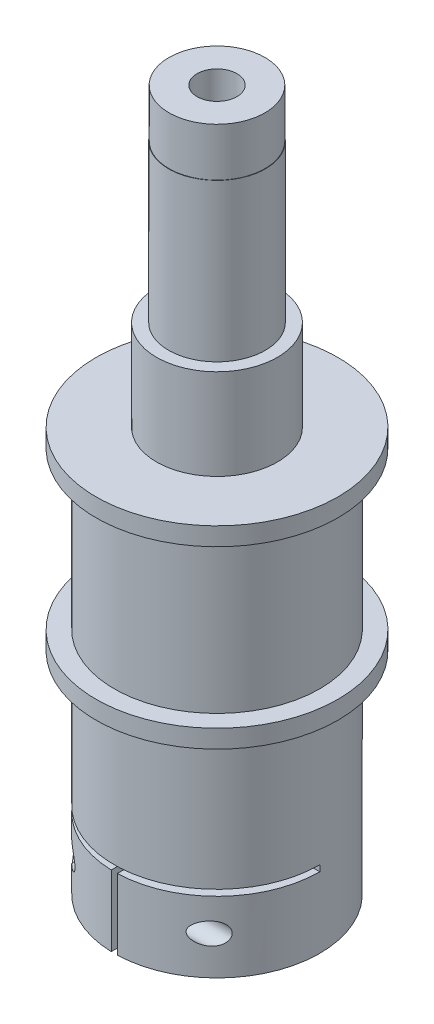
SolidWorks part; units mm, degrees
material "6061 Alloy"
ref_plane "Front Plane" through (0, 0, 0) normal (0, 0, 1) x (1, 0, 0)
ref_plane "Top Plane" through (0, 0, 0) normal (0, 1, 0) x (1, 0, 0)
ref_plane "Right Plane" through (0, 0, 0) normal (1, 0, 0) x (0, 0, -1)
sketch "Sketch1" plane through (0, 0, 0) normal (0, 0, 1) x (1, 0, 0)
  line L2 (-8.5, -17.45) -> (-8.5, 0)
  line L3 (-8.5, 0) -> (-10, 0)
  line L4 (-10, 0) -> (-10, 1.5)
  line L5 (-10, 1.5) -> (-8.5, 1.5)
  line L6 (-8.5, 1.5) -> (-8.5, 14.5)
  line L7 (-8.5, 14.5) -> (-10, 14.5)
  line L8 (-10, 14.5) -> (-10, 16)
  line L10 (0, 40.5) -> (0, 2.55)
  line L11 (-4, -17.45) -> (-8.5, -17.45)
  line L12 (-4, 2.55) -> (-4, -17.45)
  line L13 (0, 2.55) -> (-4, 2.55)
  line L15 (-3.9688, 36.5) -> (-3.9688, 40.5)
  line L16 (-3.9688, 40.5) -> (0, 40.5)
  line L17 (-10, 16) -> (-5, 16)
  line L19 (-4, 36.5) -> (-3.9688, 36.5)
  line L20 (-4, 36.5) -> (-4, 23.5)
  line L21 (-4, 23.5) -> (-5, 23.5)
  line L22 (-5, 23.5) -> (-5, 16)
  point P0 (0, 0)
  dimension "D1" = 8.5
  dimension "D2" = 1.5
  dimension "D3" = 17.45
  dimension "D4" = 1.5
  dimension "D5" = 4
  dimension "D6" = 20
  dimension "D7" = 3.9688
  dimension "D8" = 10
  dimension "D9" = 16
  dimension "D10" = 4
  dimension "D11" = 4
  dimension "D12" = 5
  dimension "D13" = 7.5
  dimension "D14" = 13
revolve "Revolve1" add sketch "Sketch1" angle 360 about L10
ref_plane "Plane1" through (-8.5, 0, 0) normal (-1, 0, 0) x (0, 0, 1)
hole_wizard "CBORE for M1.6 SHCS1" positions "Sketch2" profile "Sketch3" counterbore size "M1.6" standard "ANSI Metric" end condition through all
sketch "Sketch2" plane through (-8.5, 0, 0) normal (1, 0, 0) x (0, 0, -1)
  line L0 (-8.5, -17.45) -> (8.5, -17.45) construction
  point P0 (-6.25, -14.275)
  dimension "D1" = 6.25
  dimension "D2" = 3.175
sketch "Sketch3" plane through (-8.5, -14.275, 6.25) normal (0, 1, 0) x (0, 0, 1)
  line L0 (0, 0) -> (0, 18.5)
  line L1 (0, 18.5) -> (0.9, 18.5)
  line L3 (0.9, 18.5) -> (0.9, 2.6)
  line L4 (0.9, 2.6) -> (1.75, 2.6)
  line L5 (1.75, 2.6) -> (1.75, 0)
  line L7 (1.75, 0) -> (0, 0)
  line L11 (0, -6.35) -> (0, 107.95) construction
  dimension "Thru Hole Dia." = 1.8
  dimension "Thru Hole Depth" = 18.5
  dimension "C'Bore Dia." = 3.5
  dimension "C'Bore Depth" = 2.6
sketch "Sketch4" plane through (0, 0, 0) normal (0, 1, 0) x (1, 0, 0)
  line L0 (-0.25, -8.5) -> (-0.25, 0)
  line L1 (-0.25, -8.5) -> (0.25, -8.5)
  line L2 (-0.25, 0) -> (0.25, 0)
  line L3 (0.25, -8.5) -> (0.25, 0)
  line L4 (-0.25, -8.5) -> (0.25, 0) construction
  line L5 (-0.25, 0) -> (0.25, -8.5) construction
  circle A0 centre (0, 0) radius 8.5 construction
  point P1 (0, -4.25)
  dimension "D1" = 0.5
extrude "Cut-Extrude1" cut sketch "Sketch4" against normal up to next from offset 11.1 offset against normal yes
sketch "Sketch5" plane through (0, 0, 0) normal (0, 0, 1) x (1, 0, 0)
  line L0 (-9, -11.6) -> (-9, -11.1)
  line L1 (-9, -11.6) -> (9, -11.6)
  line L2 (-9, -11.1) -> (9, -11.1)
  line L3 (9, -11.6) -> (9, -11.1)
  line L4 (-9, -11.6) -> (9, -11.1) construction
  line L5 (-9, -11.1) -> (9, -11.6) construction
  point P1 (0, -11.35)
  dimension "D1" = 0.5
  dimension "D2" = 18
  dimension "D3" = 11.1
extrude "Cut-Extrude2" cut sketch "Sketch5" along normal through all
hole_wizard "M4x0.7 Tapped Hole1" positions "Sketch6" profile "Sketch8" tap size "M4x0.7" standard "ANSI Metric"
sketch "Sketch6" plane through (0, 40.5, 0) normal (0, 1, 0) x (1, 0, 0)
  point P0 (0, 0)
sketch "Sketch8" plane through (0, 40.5, 0) normal (1, 0, 0) x (0, 0, 1)
  line L0 (0, 0) -> (0, 11.0914)
  line L1 (0, 11.0914) -> (1.65, 10.1)
  line L2 (1.65, 10.1) -> (1.65, 0)
  line L5 (1.65, 0) -> (0, 0)
  line L10 (0, 11.0914) -> (-1.65, 10.1) construction
  line L11 (0, -6.35) -> (0, 107.95) construction
  dimension "Tap Drill Dia." = 3.3
  dimension "Tap Drill Depth" = 10.1
  dimension "Drill Angle" = 118
cosmetic thread "Hole Thread1" parameters "D1"=8, "D2"=4
